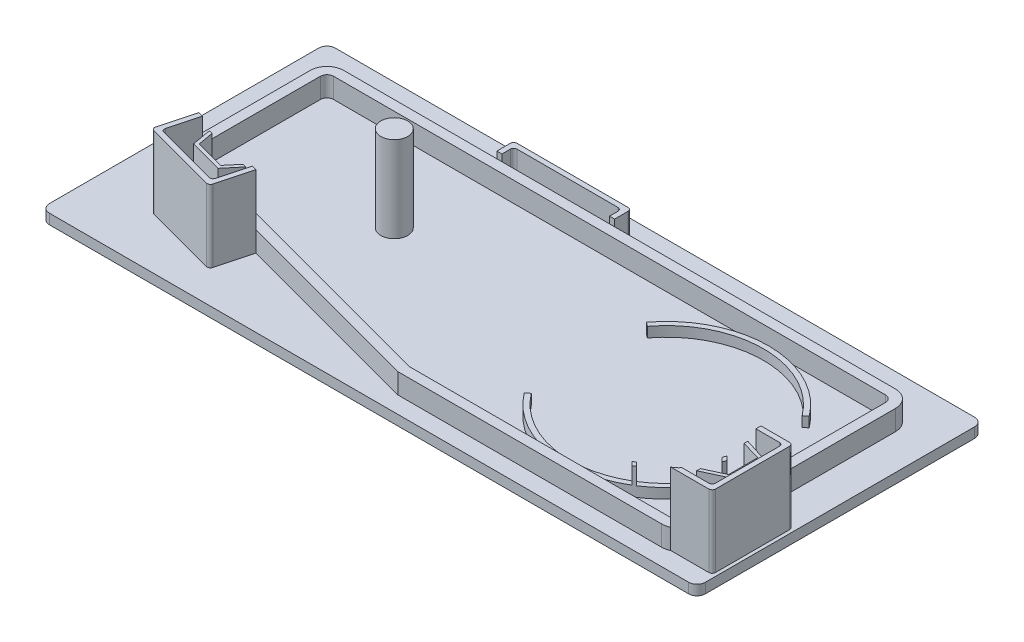
SolidWorks part; units mm, degrees
ref_plane "Front" through (0, 0, 0) normal (0, 0, 1) x (1, 0, 0)
ref_plane "Top" through (0, 0, 0) normal (0, 1, 0) x (1, 0, 0)
ref_plane "Right" through (0, 0, 0) normal (1, 0, 0) x (0, 0, -1)
sketch "Sketch1" plane through (0, 0, 0) normal (0, 1, 0) x (1, 0, 0)
  line L1 (-97.5, 42.5) -> (97.5, 42.5)
  line L2 (-97.5, 42.5) -> (-97.5, -42.5)
  line L3 (-97.5, -42.5) -> (97.5, -42.5)
  line L4 (97.5, 42.5) -> (97.5, -42.5)
  line L5 (-97.5, 42.5) -> (97.5, -42.5) construction
  line L6 (-97.5, -42.5) -> (97.5, 42.5) construction
  point P0 (0, 0)
  dimension "D1" = 85
  dimension "D2" = 195
extrude "Boss-Extrude1" add sketch "Sketch1" along normal blind 3
fillet "Fillet1" radius 2.5 4 edges at (97.5, 1.5, -42.5) (97.5, 1.5, 42.5) (-97.5, 1.5, -42.5) (-97.5, 1.5, 42.5)
sketch "Sketch2" plane through (0, 3, 0) normal (0, 1, 0) x (1, 0, 0)
  line L0 (-63.593, -10.9205) -> (-64.96, -16.0222) construction
  line L2 (-84, -10.9205) -> (-84, 23.5) construction
  line L3 (-84, 23.5) -> (84, 23.5) construction
  line L4 (84, -23.5) -> (84, 23.5) construction
  line L5 (-61.0325, -17.0746) -> (84, 23.5) construction
  line L6 (-84, 23.5) -> (84, -23.5) construction
  line L7 (84, -34.5) -> (84, 29) construction
  line L8 (4, 34.5) -> (4, -46.008) construction
  line L9 (84, -34.5) -> (4, -34.5) construction
  line L10 (-74, -10.9205) -> (-74, -17.0746) construction
  line L11 (-4, 34.5) -> (-34, 34.5) construction
  line L12 (-84, 29) -> (-84, 23.5) construction
  line L13 (-74, -13.6) -> (-77.1058, -25.1911) construction
  line L14 (-77.1058, -25.1911) -> (-58.7532, -30.1086) construction
  line L15 (-58.7532, -30.1086) -> (-55.6474, -18.5175) construction
  line L16 (-67.9295, -27.6499) -> (-64.8237, -16.0587) construction
  line L18 (84, -24.5) -> (126.6651, -24.5) construction
  line L19 (84, -15.5) -> (94, -15.5) construction
  line L20 (94, -15.5) -> (94, -34.5) construction
  line L21 (84, -33.5) -> (103.3714, -33.5) construction
  line L22 (-19, 29) -> (-19, 23.5) construction
  line L23 (-34, 23.5) -> (-4, 23.5) construction
  line L24 (-34, 23.5) -> (-34, 34.5) construction
  line L25 (-34, 34.5) -> (-4, 34.5) construction
  line L26 (-4, 34.5) -> (-4, 23.5) construction
  line L27 (84, 29) -> (-84, 29) construction
  line L28 (97.5, -40) -> (97.5, 40) construction
  line L29 (95, 42.5) -> (-95, 42.5) construction
  line L32 (4, -34.5) -> (-84, -10.9205) construction
  line L33 (-84, -10.9205) -> (-27.949, -10.9205) construction
  circle A0 centre (-19, 29) radius 2.5
  point P0 (0, 0)
  point P38 (-34, 29)
  dimension "D5" = 5
  dimension "D6" = 65
  dimension "D8" = 12
  dimension "D2" = 29
  dimension "D3" = 168
  dimension "D4" = 80
  dimension "D7" = 10
  dimension "D9" = 19
  dimension "D10" = 84
  dimension "D11" = 23.5
  dimension "D12" = 9
  dimension "D13" = 9
  dimension "D14" = 10
  dimension "D15" = 63.5
  dimension "D16" = 11
  dimension "D17" = 15
  dimension "D18" = 15
  dimension "D19" = 10
  dimension "D22" = 15
sketch "Sketch3" plane through (0, 3, 0) normal (0, 1, 0) x (1, 0, 0)
  line L0 (-84, -9.3858) -> (-84, 27)
  line L2 (84, 27) -> (84, -32.5)
  line L3 (82, -34.5) -> (4, -34.5)
  line L7 (82, -37.5) -> (4, -37.5)
  line L10 (84, 29) -> (-84, 29) construction
  line L11 (82, 29) -> (-82, 29)
  line L12 (-82, 37.5) -> (82, 37.5) construction
  line L13 (-82, 34.5) -> (82, 34.5) construction
  line L14 (87, 32.5) -> (87, -32.5) construction
  line L15 (84, 32.5) -> (84, -32.5) construction
  line L16 (-84, -21.7344) -> (-84, 32.5) construction
  line L17 (-87, -21.7344) -> (-87, 32.5) construction
  line L19 (-81.8759, 32) -> (82, 32)
  line L20 (87, 27) -> (87, -32.5)
  line L21 (4, -34.5) -> (-84, -10.9205) construction
  line L22 (4, -34.5) -> (-82.5176, -11.3177)
  line L23 (3.8132, -37.5) -> (-82.6202, -26.6958) construction
  line L24 (4, -34.5) -> (-82.2481, -23.719) construction
  line L27 (4, -34.5) -> (4, -37.5) construction
  line L29 (82, -37.5) -> (3.8132, -37.5) construction
  line L30 (-81.8759, 32) -> (-82, 32)
  line L31 (-87, 27) -> (-87, -9.3858)
  line L32 (-80.2401, -15.0338) -> (-13.0959, -33.025)
  line L33 (-13.0959, -33.025) -> (3.605, -37.5)
  line L34 (4, -37.5) -> (3.605, -37.5)
  line L35 (-80.2401, -15.0338) -> (-83.2941, -14.2154)
  arc A1 (84, -32.5) -> (82, -34.5) centre (82, -32.5) cw
  arc A6 (87, -32.5) -> (82, -37.5) centre (82, -32.5) cw
  arc A8 (82, 34.5) -> (84, 32.5) centre (82, 32.5) cw construction
  arc A9 (82, 37.5) -> (87, 32.5) centre (82, 32.5) cw construction
  arc A10 (-87, 32.5) -> (-82, 37.5) centre (-82, 32.5) cw construction
  arc A11 (-84, 32.5) -> (-82, 34.5) centre (-82, 32.5) cw construction
  arc A12 (82, 29) -> (84, 27) centre (82, 27) cw
  arc A13 (-82, 29) -> (-84, 27) centre (-82, 27) ccw
  arc A14 (82, 32) -> (87, 27) centre (82, 27) cw
  arc A16 (-87, -21.7344) -> (-82.6202, -26.6958) centre (-82, -21.7344) ccw construction
  arc A17 (-84, -21.7344) -> (-82.2481, -23.719) centre (-82, -21.7344) ccw construction
  arc A18 (-82, 32) -> (-87, 27) centre (-82, 27) ccw
  arc A19 (-87, -9.3858) -> (-83.2941, -14.2154) centre (-82, -9.3858) ccw
  arc A20 (-82.5176, -11.3177) -> (-84, -9.3858) centre (-82, -9.3858) cw
  point P15 (84, -34.5)
  dimension "D1" = 3
  dimension "D3" = 2
  dimension "D4" = 5
  dimension "D7" = 5
  dimension "D8" = 2
  dimension "D5" = 3
  dimension "D6" = 3
  dimension "D2" = 3
extrude "Boss-Extrude2" add sketch "Sketch3" along normal blind 6
sketch "Sketch4" plane through (0, 3, 0) normal (0, 1, 0) x (1, 0, 0)
  line L0 (-34, 23.5) -> (-34, 34.5) construction
  line L1 (-34, 34.5) -> (-4, 34.5) construction
  line L2 (-4, 34.5) -> (-4, 23.5) construction
  line L5 (-35, 35.5) -> (-35, 32)
  line L8 (-35, 35.5) -> (-3, 35.5)
  line L9 (82, 32) -> (-82, 32) construction
  line L11 (-36.5, 37) -> (-3, 37)
  line L16 (-36.5, 37) -> (-36.5, 32)
  line L24 (-36.5, 32) -> (-35, 32)
  line L25 (-3, 35.5) -> (-3, 32)
  line L26 (82, 32) -> (-82, 32) construction
  line L27 (-3, 32) -> (-1.5, 32)
  line L28 (-1.5, 32) -> (-1.5, 37)
  line L29 (-1.5, 37) -> (-3, 37)
  point P14 (-1.5, 34.5)
  dimension "D3" = 1
  dimension "D4" = 1.5
  dimension "D1" = 1.5
  dimension "D2" = 1
  dimension "D5" = 1
  dimension "D6" = 1.5
extrude "Boss-Extrude3" add sketch "Sketch4" along normal blind 8
sketch "Sketch5" plane through (0, 3, 0) normal (0, 1, 0) x (1, 0, 0)
  line L0 (84, -24.5) -> (126.6651, -24.5) construction
  line L16 (93.7176, -28.9709) -> (93.7176, -19.0291)
  line L17 (87.4445, -17.0409) -> (87, -16.9)
  line L18 (87.4226, -31.9063) -> (93.7176, -28.9709)
  line L19 (87.4226, -31.9063) -> (87, -32.1034)
  line L20 (92.7176, -19.6661) -> (87, -18)
  line L21 (87, -32.1034) -> (87, -31)
  line L22 (87, -31) -> (92.7176, -28.3339)
  line L23 (93.7176, -19.0291) -> (87.4445, -17.0409)
  line L24 (87, -16.9) -> (87, -18)
  line L25 (92.7176, -28.3339) -> (92.7176, -19.6661)
  line L26 (87, -15.5) -> (87, -30.4107) construction
  line L27 (84, -15.5) -> (94, -15.5) construction
  line L31 (-71.8787, -17.2742) -> (-71.0569, -21.9347)
  line L32 (-83.2941, -14.2154) -> (3.605, -37.5) construction
  line L33 (-71.0569, -21.9347) -> (-62.3636, -24.2641)
  line L34 (-62.3636, -24.2641) -> (-59.3216, -20.6388)
  line L35 (-83.2941, -14.2154) -> (3.605, -37.5) construction
  line L36 (-67.9295, -27.6499) -> (-64.8237, -16.0587) construction
  line L37 (-72.8635, -17.4478) -> (-71.9311, -22.7357)
  line L38 (-71.9311, -22.7357) -> (-62.007, -25.3949)
  line L39 (-62.007, -25.3949) -> (-58.5556, -21.2816)
  line L40 (-72.8635, -17.4478) -> (-72.9445, -16.9886)
  line L41 (-72.9445, -16.9886) -> (-71.8787, -17.2742)
  line L42 (-58.5556, -21.2816) -> (-58.2559, -20.9244)
  line L43 (-58.2559, -20.9244) -> (-59.3216, -20.6388)
  dimension "D7" = 6.5
  dimension "D8" = 6.5
  dimension "D9" = 65
  dimension "D10" = 65
  dimension "D11" = 9
  dimension "D2" = 6.5
  dimension "D3" = 6.5
  dimension "D4" = 1
  dimension "D5" = 1.1
  dimension "D6" = 1
  dimension "D13" = 8.6677
  dimension "D12" = 1
extrude "Boss-Extrude4" add sketch "Sketch5" along normal blind 19.5
sketch "Sketch6" plane through (0, 3, 0) normal (0, 1, 0) x (1, 0, 0)
  line L3 (84, -34.5) -> (94, -34.5) construction
  line L4 (94, -34.5) -> (94, -15.5) construction
  line L5 (94, -15.5) -> (84, -15.5) construction
  line L7 (-74, -13.6) -> (-77.1058, -25.1911) construction
  line L13 (87, -16.9) -> (87, 27) construction
  line L15 (87, -16.9) -> (87, 27) construction
  line L16 (95, -35.5) -> (95, -14.5)
  line L17 (95, -14.5) -> (87, -14.5)
  line L18 (-77.1058, -25.1911) -> (-58.7532, -30.1086) construction
  line L20 (84.1794, -37) -> (96.5, -37)
  line L21 (96.5, -37) -> (96.5, -13)
  line L22 (96.5, -13) -> (87, -13)
  line L24 (86, -35.5) -> (95, -35.5)
  line L31 (87, -13) -> (87, -14.5)
  line L32 (-58.7532, -30.1086) -> (-55.6474, -18.5175) construction
  line L33 (-64.8237, -16.0587) -> (-67.9295, -27.6499) construction
  line L34 (-75.7424, -16.2389) -> (-78.3306, -25.8982)
  line L35 (-83.2941, -14.2154) -> (-72.9445, -16.9886) construction
  line L36 (-67.9295, -27.6499) -> (-67.7748, -27.0724) construction
  line L37 (-78.3306, -25.8982) -> (-68.1884, -28.6158)
  line L38 (-77.1913, -15.8507) -> (-80.1677, -26.9588)
  line L39 (-80.1677, -26.9588) -> (-68.5766, -30.0647)
  line L40 (-56.9855, -33.1705) -> (-68.5766, -30.0647)
  line L41 (-54.0091, -22.0623) -> (-56.9855, -33.1705)
  line L42 (-58.0461, -31.3334) -> (-68.1884, -28.6158)
  line L43 (-55.4579, -21.6741) -> (-58.0461, -31.3334)
  line L44 (-77.1913, -15.8507) -> (-75.7424, -16.2389)
  line L45 (-55.4579, -21.6741) -> (-54.0091, -22.0623)
  arc A0 (82, -37.5) -> (87, -32.5) centre (82, -32.5) ccw construction
  arc A1 (84.1794, -37) -> (86, -35.5) centre (82, -32.5) ccw
  dimension "D7" = 1.5
  dimension "D8" = 1.5
  dimension "D9" = 1
  dimension "D10" = 24
  dimension "D11" = 1.5
  dimension "D12" = 1
  dimension "D13" = 1
  dimension "D14" = 1
  dimension "D15" = 1.5
extrude "Boss-Extrude5" add sketch "Sketch6" along normal blind 21.5
fillet "Fillet2" radius 1 12 edges at (-36.5, 7, -37) (95, 13.75, 14.5) (95, 13.75, 35.5) (96.5, 13.75, 13) (96.5, 13.75, 37) (-1.5, 7, -37) (-3, 7, -35.5) (-35, 7, -35.5) (-58.0461, 13.75, 31.3334) (-78.3306, 13.75, 25.8982) (-80.1677, 13.75, 26.9588) (-56.9855, 13.75, 33.1705)
sketch "Sketch7" plane through (0, 3, 0) normal (0, 1, 0) x (1, 0, 0)
  line L0 (-52.2946, 5) -> (-21.1099, 5) construction
  line L1 (84, 29) -> (-84, 29) construction
  line L2 (49, -3) -> (5.7829, -3) construction
  line L3 (49, -3) -> (49, 37.3798) construction
  line L4 (84, -23.5) -> (84, 23.5) construction
  circle A0 centre (-40, 5) radius 4
  circle A1 centre (49, -3) radius 28.75 construction
  dimension "D2" = 8
  dimension "D4" = 57.5
  dimension "D1" = 5
  dimension "D3" = 40
  dimension "D5" = 32
  dimension "D6" = 35
extrude "Boss-Extrude6" add sketch "Sketch7" along normal blind 25.5
sketch "Sketch8" plane through (0, 3, 0) normal (0, 1, 0) x (1, 0, 0)
  line L0 (49, -3) -> (49, 37.3798) construction
  line L1 (49, -3) -> (5.7829, -3) construction
  line L2 (49, -3) -> (49, 37.3798) construction
  line L3 (49, -3) -> (5.7829, -3) construction
  line L4 (24.8, 15.15) -> (26, 14.25)
  line L5 (72, 14.25) -> (73.2, 15.15)
  line L6 (24.8, -21.15) -> (26, -20.25)
  line L7 (72, -20.25) -> (73.2, -21.15)
  line L8 (26, 14.25) -> (72, 14.25) construction
  circle A0 centre (49, -3) radius 28.75 construction
  circle A1 centre (49, -3) radius 28.75 construction
  arc A2 (26, 14.25) -> (72, 14.25) centre (49, -3) cw
  arc A3 (24.8, 15.15) -> (73.2, 15.15) centre (49, -3) cw
  arc A4 (24.8, -21.15) -> (73.2, -21.15) centre (49, -3) ccw
  arc A5 (26, -20.25) -> (72, -20.25) centre (49, -3) ccw
  dimension "D2" = 46
  dimension "D1" = 1.5
extrude "Boss-Extrude7" add sketch "Sketch8" along normal blind 3
sketch "Sketch9" plane through (0, 3, 0) normal (0, 1, 0) x (1, 0, 0)
  line L0 (66.6881, -27.5396) -> (66.6881, -27.5396)
  line L1 (64.364, -27.3004) -> (65.4499, -28.3863)
  line L2 (63.4842, -27.8349) -> (64.5791, -28.9298)
  line L5 (76.1999, -12.3129) -> (77.374, -13.4871)
  line L6 (75.8225, -13.3498) -> (76.977, -14.5043)
  arc A0 (75.8225, -13.3498) -> (76.1999, -12.3129) centre (49, -3) ccw
  circle A1 centre (49, -3) radius 28.75 construction
  arc A2 (63.4842, -27.8349) -> (64.364, -27.3004) centre (49, -3) ccw
  arc A3 (64.5791, -28.9298) -> (65.4499, -28.3863) centre (49, -3) ccw
  arc A4 (76.977, -14.5043) -> (77.374, -13.4871) centre (49, -3) ccw
  arc A5 (66.6881, -27.5396) -> (77.619, -12.7988) centre (49, -3) ccw construction
  arc A6 (64.364, -27.3004) -> (76.1999, -12.3129) centre (49, -3) ccw construction
  dimension "D5" = 28.75
  dimension "D6" = 30.25
  dimension "D1" = 1.5
  dimension "D2" = 1
  dimension "D3" = 1
  dimension "D4" = 18.044
  dimension "D7" = 1.5357
  dimension "D8" = 1.6328
extrude "Boss-Extrude8" add sketch "Sketch9" along normal blind 8 contours L1 A3 L2 A2 | A4 L5 A0 L6
equation "\"D5@Sketch4\"=\"D2@Sketch4\""
equation "\"D6@Sketch4\"=\"D4@Sketch4\""
equation "\"D8@Sketch5\"=\"D7@Sketch5\""
equation "\"D10@Sketch5\"=\"D9@Sketch5\""
equation "\"D3@Sketch5\"=\"D2@Sketch5\""
